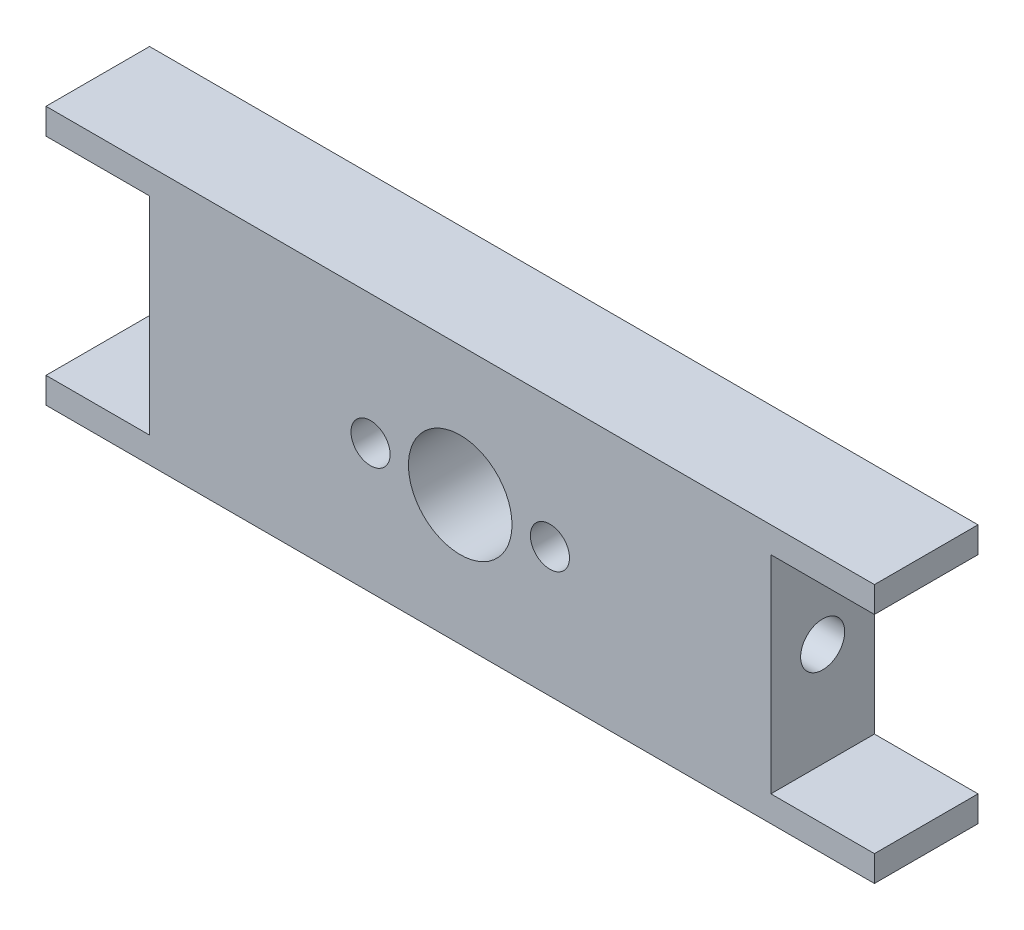
SolidWorks part; units mm, degrees
material "6061-T6 (SS)"
ref_plane "Front Plane" through (0, 0, 0) normal (0, 0, 1) x (1, 0, 0)
ref_plane "Top Plane" through (0, 0, 0) normal (0, 1, 0) x (1, 0, 0)
ref_plane "Right Plane" through (0, 0, 0) normal (1, 0, 0) x (0, 0, -1)
sketch "Sketch1" plane through (0, 0, 0) normal (0, 0, 1) x (1, 0, 0)
  line L0 (25.4, -6.35) -> (25.4, -7.9375)
  line L1 (25.4, 7.9375) -> (-25.4, 7.9375)
  line L2 (25.4, 7.9375) -> (25.4, 6.35)
  line L3 (25.4, -7.9375) -> (-25.4, -7.9375)
  line L4 (-25.4, 7.9375) -> (-25.4, 6.35)
  line L5 (25.4, 6.35) -> (19.05, 6.35)
  line L6 (-25.4, -6.35) -> (-25.4, -7.9375)
  line L7 (25.4, -6.35) -> (19.05, -6.35)
  line L8 (19.05, 6.35) -> (19.05, -6.35)
  line L9 (-25.4, 6.35) -> (-19.05, 6.35)
  line L11 (-25.4, -6.35) -> (-19.05, -6.35)
  line L12 (-19.05, 6.35) -> (-19.05, -6.35)
  circle A0 centre (0, 0) radius 3.175
  dimension "D1" = 6.35
  dimension "D2" = 15.875
  dimension "D3" = 25.4
  dimension "D4" = 6.35
  dimension "D5" = 1.5875
  dimension "D6" = 1.5875
  dimension "D7" = 50.8
  dimension "D8" = 1.5875
  dimension "D9" = 1.5875
  dimension "D10" = 6.35
  dimension "D11" = 7.9375
extrude "Boss-Extrude1" add sketch "Sketch1" along normal blind 6.35
hole_wizard "Tap Drill for #6-32 Tap1" positions "Sketch3" profile "Sketch4" hole size "#6-32" standard "ANSI Inch"
sketch "Sketch3" plane through (19.05, 0, 0) normal (1, 0, 0) x (0, 0, -1)
  point P3 (-3.175, 0)
sketch "Sketch4" plane through (19.05, 0, 3.175) normal (0, 1, 0) x (0, 0, -1)
  line L0 (0, 0) -> (0, 7.1627)
  line L1 (0, 7.1627) -> (1.3525, 6.35)
  line L2 (1.3525, 6.35) -> (1.3525, 0)
  line L5 (1.3525, 0) -> (0, 0)
  line L10 (0, 7.1627) -> (-1.3526, 6.35) construction
  line L11 (0, -6.35) -> (0, 107.95) construction
  dimension "Hole Dia." = 2.7051
  dimension "Hole Depth" = 6.35
  dimension "Drill Angle" = 118
hole_wizard "M2 Clearance Hole1" positions "Sketch6" profile "Sketch5" hole size "M2" standard "ANSI Metric" end condition through all
sketch "Sketch6" plane through (0, 0, 0) normal (0, 0, -1) x (-1, 0, 0)
  circle A0 centre (0, 0) radius 3.175 construction
  point P0 (-5.5, 0)
  point P2 (5.5, 0)
  dimension "D1" = 5.5
  dimension "D2" = 5.5
sketch "Sketch5" plane through (5.5, 0, 0) normal (1, 0, 0) x (0, 1, 0)
  line L0 (0, 0) -> (0, 6.35)
  line L1 (0, 6.35) -> (1.2, 6.35)
  line L2 (1.2, 6.35) -> (1.2, 0.025)
  line L3 (1.2, 0.025) -> (1.225, 0)
  line L5 (1.225, 0) -> (0, 0)
  line L6 (-1.2, 0.025) -> (-1.225, 0) construction
  line L11 (0, -6.35) -> (0, 107.95) construction
  dimension "Thru Hole Dia." = 2.4
  dimension "Thru Hole Depth" = 6.35
  dimension "Near C'Sink Dia." = 2.45
  dimension "Near C'Sink Angle" = 90
ref_plane "Plane1" through (0, 0, 0) normal (-1, 0, 0) x (0, 0, 1)
mirror "Mirror1" about plane through (0, 0, 0) normal (-1, 0, 0) of "Tap Drill for #6-32 Tap1"
equation "\"D11@Sketch1\"=\"D2@Sketch1\"/2"
equation "\"D2@Sketch6\"=\"D1@Sketch6\""
